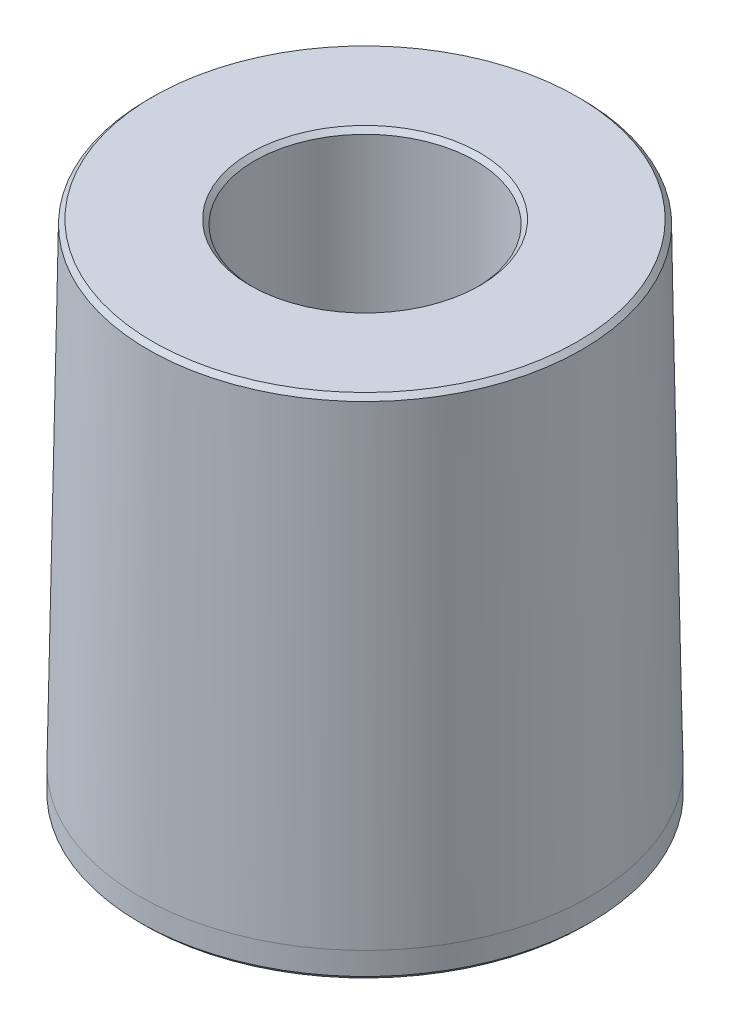
SolidWorks part; units mm, degrees
material "Żeliwo ciągliwe"
ref_plane "Płaszczyzna przednia" through (0, 0, 0) normal (0, 0, 1) x (1, 0, 0)
ref_plane "Płaszczyzna górna" through (0, 0, 0) normal (0, 1, 0) x (1, 0, 0)
ref_plane "Płaszczyzna prawa" through (0, 0, 0) normal (1, 0, 0) x (0, 0, -1)
sketch "Szkic1" plane through (0, 0, 0) normal (0, 0, 1) x (1, 0, 0)
  line L0 (0, 0) -> (0, 92.9175) construction
  line L1 (-48, 104.9604) -> (-48, -11.6576) construction
  line L2 (-24.45, 14.9604) -> (-24.45, 104.9604)
  line L3 (-24.45, 104.9604) -> (-24.45, -6.0396) construction
  line L4 (-48, 104.9604) -> (-49.8328, -0.0396)
  line L5 (-21.45, 60.1164) -> (-21.45, -31.1328) construction
  line L6 (-48, 104.9604) -> (-24.45, 104.9604)
  line L7 (-66.9486, 13.9604) -> (72.9751, 13.9604) construction
  line L8 (-23.45, 13.9604) -> (-23.45, -6.0396)
  line L9 (-23.45, -6.0396) -> (-49.8328, -6.0396)
  line L10 (-49.8328, -6.0396) -> (-49.8328, -0.0396)
  arc A0 (-24.45, 14.9604) -> (-23.45, 13.9604) centre (-23.45, 14.9604) ccw
  dimension "D9" = 23.45
  dimension "D8" = 1
  dimension "D1" = 111
  dimension "D2" = 24.45
  dimension "D3" = 1
  dimension "D5" = 48
  dimension "D6" = 6
  dimension "D7" = 91
revolve "Obrót1" add sketch "Szkic1" angle 360 about L0
chamfer "Sfazowanie1" distance 1 angle 45 4 edges at (49.8328, -6.0396, 0) (23.45, -6.0396, 0) (24.45, 104.9604, 0) (48, 104.9604, 0)
